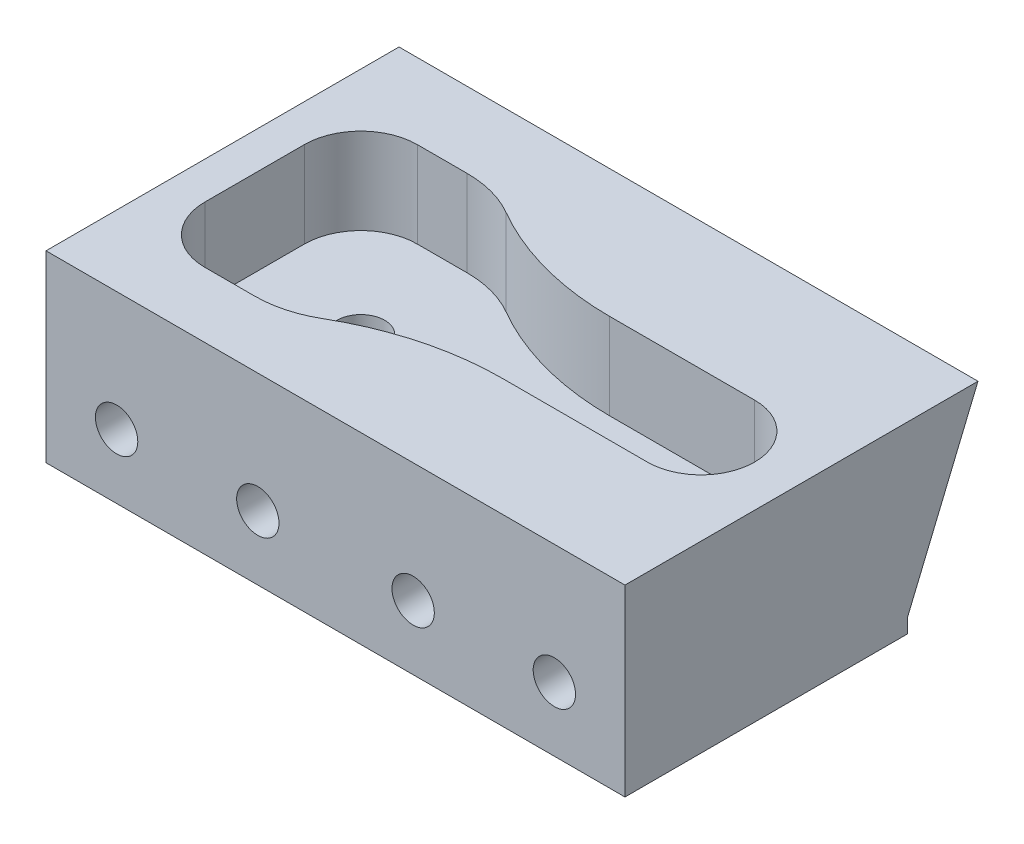
SolidWorks part; units mm, degrees
ref_plane "Front Plane" through (0, 0, 0) normal (0, 0, 1) x (1, 0, 0)
ref_plane "Top Plane" through (0, 0, 0) normal (0, 1, 0) x (1, 0, 0)
ref_plane "Right Plane" through (0, 0, 0) normal (1, 0, 0) x (0, 0, -1)
sketch "Sketch1" plane through (0, 0, 0) normal (0, 1, 0) x (1, 0, 0)
  line L1 (0, 0) -> (41, 0)
  line L2 (0, 0) -> (0, 25)
  line L3 (0, 25) -> (41, 25)
  line L4 (41, 0) -> (41, 25)
  dimension "D1" = 25
  dimension "D2" = 41
extrude "Boss-Extrude1" add sketch "Sketch1" along normal blind 13
sketch "Sketch2" plane through (0, 0, 0) normal (0, 0, 1) x (1, 0, 0)
  line L0 (0, 0) -> (41, 0) construction
  line L1 (0, 13) -> (0, 0) construction
  circle A0 centre (5, 4.545) radius 1.5
  dimension "D1" = 3
  dimension "D2" = 4.545
  dimension "D3" = 5
extrude "Cut-Extrude1" cut sketch "Sketch2" against normal through all
pattern_linear "LPattern1" count 2 spacing 10 along (1, 0, 0) of "Cut-Extrude1"
pattern_linear "LPattern3" count 2 spacing 21 along (1, 0, 0) of "Cut-Extrude1"
sketch "Sketch8" plane through (0, 0, 0) normal (0, 0, 1) x (1, 0, 0)
  line L0 (26, 4.545) -> (36, 4.545) construction
  circle A0 centre (36, 4.545) radius 1.5
  circle A2 centre (26, 4.545) radius 1.5 construction
  point P2 (0, 0)
  dimension "D1" = 10
extrude "Cut-Extrude5" cut sketch "Sketch8" against normal blind 8
sketch "Sketch3" plane through (0, 13, 0) normal (0, 1, 0) x (1, 0, 0)
  line L0 (34.25, 12.135) -> (10.16, 12.135) construction
  line L1 (34.25, 8.335) -> (10.16, 8.335)
  line L2 (34.25, 15.935) -> (10.16, 15.935)
  line L3 (0, 0) -> (41, 0) construction
  line L4 (0, 25) -> (0, 0) construction
  line L5 (10.16, 4.61) -> (6.635, 4.61)
  line L6 (10.16, 4.61) -> (10.16, 19.66)
  line L7 (10.16, 19.66) -> (6.635, 19.66)
  line L8 (2.635, 8.61) -> (2.635, 15.66)
  circle A1 centre (10.16, 12.135) radius 7.525
  arc A2 (34.25, 8.335) -> (34.25, 15.935) centre (34.25, 12.135) ccw
  arc A3 (10.16, 15.935) -> (10.16, 8.335) centre (10.16, 12.135) ccw
  arc A4 (6.635, 19.66) -> (2.635, 15.66) centre (6.635, 15.66) ccw
  arc A5 (6.635, 4.61) -> (2.635, 8.61) centre (6.635, 8.61) cw
  point P1 (22.205, 12.135)
  dimension "D2" = 15.05
  dimension "D6" = 4
  dimension "D1" = 12.135
  dimension "D3" = 7.6
  dimension "D4" = 10.16
  dimension "D5" = 24.09
  dimension "D8" = 31.615
extrude "Cut-Extrude2" cut sketch "Sketch3" against normal blind 6.1
hole_wizard "CBORE for M3 Hex Socket Head Cap Screw1" positions "Sketch6" profile "Sketch5" counterbore size "M3" standard "ISO" end condition through all
sketch "Sketch6" plane through (0, 0, 0) normal (0, -1, 0) x (-1, 0, 0)
  arc A2 (-16.655, 8.335) -> (-10.16, 4.61) centre (-10.16, 12.135) ccw construction
  arc A3 (-34.25, 15.935) -> (-34.25, 8.335) centre (-34.25, 12.135) ccw construction
  point P0 (-34.25, 12.135)
  point P2 (-10.16, 12.135)
sketch "Sketch5" plane through (34.25, 0, -12.135) normal (1, 0, 0) x (0, 0, -1)
  line L0 (0, 0) -> (0, 13)
  line L1 (0, 13) -> (1.7, 13)
  line L3 (1.7, 13) -> (1.7, 3.4)
  line L4 (1.7, 3.4) -> (3, 3.4)
  line L5 (3, 3.4) -> (3, 0)
  line L7 (3, 0) -> (0, 0)
  line L11 (0, -6.35) -> (0, 107.95) construction
  dimension "Thru Hole Dia." = 3.4
  dimension "Thru Hole Depth" = 13
  dimension "C'Bore Dia." = 6
  dimension "C'Bore Depth" = 3.4
fillet "Fillet1" radius 20 2 edges at (16.655, 9.95, -8.335) (16.655, 9.95, -15.935)
sketch "Sketch7" plane through (0, 0, 0) normal (-1, 0, 0) x (0, 0, 1)
  line L0 (-25, 13) -> (-20, 1)
  line L2 (-20, 1) -> (-20, 0)
  line L3 (-25, 0) -> (0, 0) construction
  line L4 (0, 13) -> (0, 0) construction
  dimension "D1" = 20
  dimension "D2" = 1
extrude "Cut-Extrude4" cut sketch "Sketch7" against normal through all and the other way through all flip side to cut
sketch "Sketch9" plane through (0, 3.4, 0) normal (0, -1, 0) x (1, 0, 0)
  line L1 (11.86, -9.135) -> (8.46, -9.135)
  line L2 (11.86, -9.135) -> (11.86, -15.135)
  line L3 (11.86, -15.135) -> (8.46, -15.135)
  line L4 (8.46, -9.135) -> (8.46, -15.135)
  circle A1 centre (10.16, -12.135) radius 1.7 construction
  circle A2 centre (10.16, -12.135) radius 3 construction
  circle M6 centre (10.16, -12.135) radius 3
extrude "Boss-Extrude3" add sketch "Sketch9" along normal blind 0.2 contours L4 M6 | L2 M6
pattern_linear "LPattern2" count 2 spacing 24.09 along (1, 0, 0) of "Boss-Extrude3"
equation "\"D2@Sketch2\"=(8-2.39+3.48)/2"
equation "\"D1@Sketch3\"=10.46+3.35/2"
